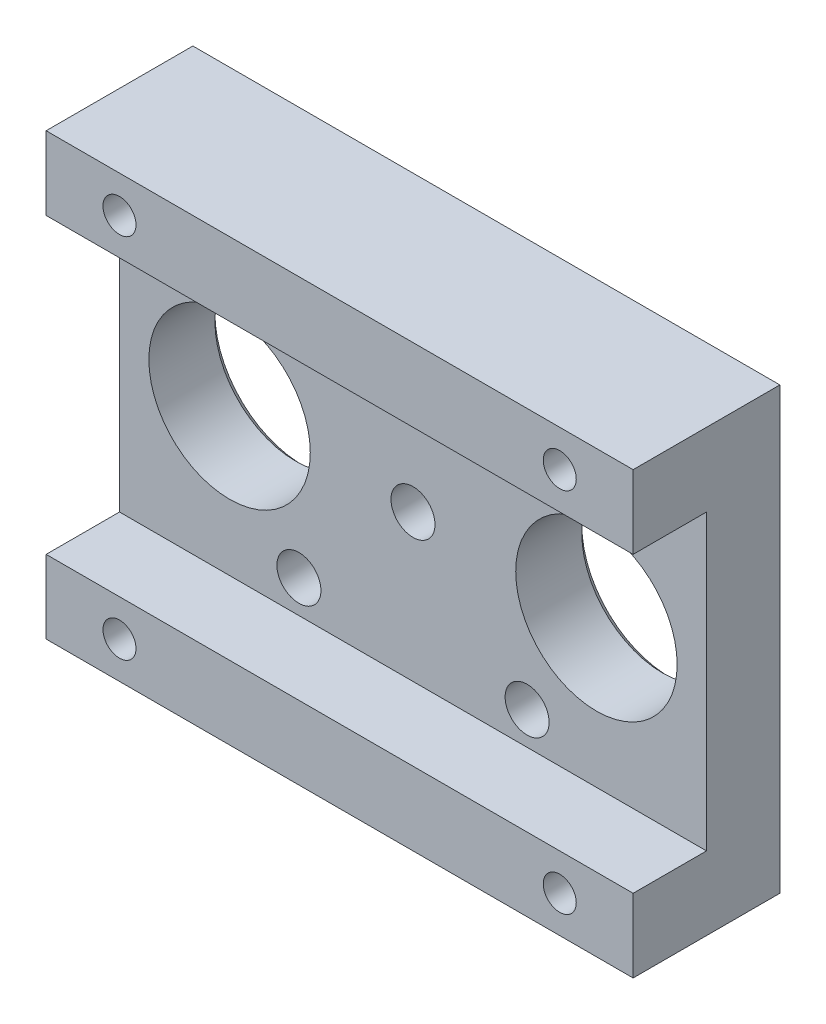
SolidWorks part; units mm, degrees
ref_plane "Ebene vorne" through (0, 0, 0) normal (0, 0, 1) x (1, 0, 0)
ref_plane "Ebene oben" through (0, 0, 0) normal (0, 1, 0) x (1, 0, 0)
ref_plane "Ebene rechts" through (0, 0, 0) normal (1, 0, 0) x (0, 0, -1)
sketch "Skizze1" plane through (0, 0, 0) normal (0, 0, 1) x (1, 0, 0)
  line L1 (-40, 30) -> (40, 30)
  line L2 (-40, 30) -> (-40, -30)
  line L3 (-40, -30) -> (40, -30)
  line L4 (40, 30) -> (40, -30)
  line L5 (-40, 30) -> (40, -30) construction
  line L6 (-40, -30) -> (40, 30) construction
  point P0 (0, 0)
  dimension "D1" = 80
  dimension "D2" = 60
extrude "Aufsatz-Linear austragen1" add sketch "Skizze1" along normal blind 10
sketch "Skizze2" plane through (0, 0, 10) normal (0, 0, 1) x (1, 0, 0)
  line L0 (40, -30) -> (40, 30) construction
  line L1 (-40, 30) -> (40, 30)
  line L2 (-40, 30) -> (-40, 20)
  line L3 (-40, 20) -> (40, 20)
  line L4 (40, 30) -> (40, 20)
  line L5 (-40, 30) -> (-40, -30) construction
  line L6 (40, -30) -> (-40, -30)
  line L7 (40, -30) -> (40, -20)
  line L8 (40, -20) -> (-40, -20)
  line L9 (-40, -30) -> (-40, -20)
  dimension "D1" = 10
  dimension "D2" = 10
extrude "Aufsatz-Linear austragen2" add sketch "Skizze2" along normal blind 10
sketch "Skizze3" plane through (0, 0, 0) normal (0, 0, -1) x (-1, 0, 0)
  circle A0 centre (0, 0) radius 11.35
  dimension "D1" = 22.7
extrude "Schnitt-Linear austragen1" cut sketch "Skizze3" against normal blind 2.2
sketch "Skizze4" plane through (0, 0, 2.2) normal (0, 0, -1) x (-1, 0, 0)
  circle A0 centre (0, 0) radius 3
extrude "Schnitt-Linear austragen2" cut sketch "Skizze4" against normal blind 12.2
sketch "Skizze5" plane through (0, 0, 20) normal (0, 0, 1) x (1, 0, 0)
  line L0 (-40, 20) -> (40, 20) construction
  line L1 (-40, -30) -> (40, -30) construction
  line L2 (40, -30) -> (40, -20) construction
  line L3 (40, 20) -> (40, 30) construction
  line L4 (-40, 30) -> (-40, 20) construction
  line L5 (-40, -20) -> (-40, -30) construction
  circle A0 centre (30, 25) radius 2.25
  circle A1 centre (-30, 25) radius 2.25
  circle A2 centre (-30, -25) radius 2.25
  circle A3 centre (30, -25) radius 2.25
  dimension "D1" = 4.5
  dimension "D2" = 4.5
  dimension "D3" = 4.5
  dimension "D4" = 4.5
  dimension "D5" = 5
  dimension "D6" = 5
  dimension "D7" = 5
  dimension "D8" = 5
  dimension "D9" = 10
  dimension "D10" = 10
  dimension "D11" = 10
  dimension "D12" = 10
extrude "Schnitt-Linear austragen3" cut sketch "Skizze5" against normal blind 12.2
sketch "Skizze6" plane through (0, 0, 10) normal (0, 0, 1) x (1, 0, 0)
  line L0 (40, -20) -> (40, 20) construction
  line L1 (-40, 20) -> (-40, -20) construction
  line L2 (-40, 20) -> (40, 20) construction
  line L3 (40, -20) -> (-40, -20) construction
  circle A0 centre (-25, 0) radius 11
  circle A1 centre (25, 0) radius 11
  dimension "D1" = 22
  dimension "D2" = 22
  dimension "D3" = 15
  dimension "D4" = 15
  dimension "D5" = 20
  dimension "D6" = 20
extrude "Schnitt-Linear austragen4" cut sketch "Skizze6" against normal blind 12.2
sketch "Skizze7" plane through (0, 0, 10) normal (0, 0, 1) x (1, 0, 0)
  line L1 (-15.55, 15.55) -> (15.55, 15.55)
  line L2 (-15.55, 15.55) -> (-15.55, -15.55)
  line L3 (-15.55, -15.55) -> (15.55, -15.55)
  line L4 (15.55, 15.55) -> (15.55, -15.55)
  line L5 (-15.55, 15.55) -> (15.55, -15.55) construction
  line L6 (-15.55, -15.55) -> (15.55, 15.55) construction
  circle A0 centre (-15.55, 15.55) radius 1.6
  circle A1 centre (15.55, 15.55) radius 1.6
  circle A2 centre (15.55, -15.55) radius 1.6
  circle A3 centre (-15.55, -15.55) radius 1.6
  point P0 (0, 0)
  dimension "D3" = 3.2
  dimension "D4" = 3.2
  dimension "D5" = 3.2
  dimension "D6" = 3.2
  dimension "D1" = 31.1
  dimension "D2" = 31.1
extrude "Schnitt-Linear austragen5" cut sketch "Skizze7" against normal blind 12.2 contours A0 | A1 | A2 | A3
sketch "Skizze8" plane through (0, 0, 10) normal (0, 0, 1) x (1, 0, 0)
  circle A0 centre (-15.55, 15.55) radius 3
  circle A1 centre (15.55, 15.55) radius 3
  circle A2 centre (-15.55, -15.55) radius 3
  circle A3 centre (15.55, -15.55) radius 3
extrude "Schnitt-Linear austragen6" cut sketch "Skizze8" against normal blind 6
chamfer "Fase1" distance 1 angle 45 2 edges at (36, 0, 0) (-14, 0, 0)
